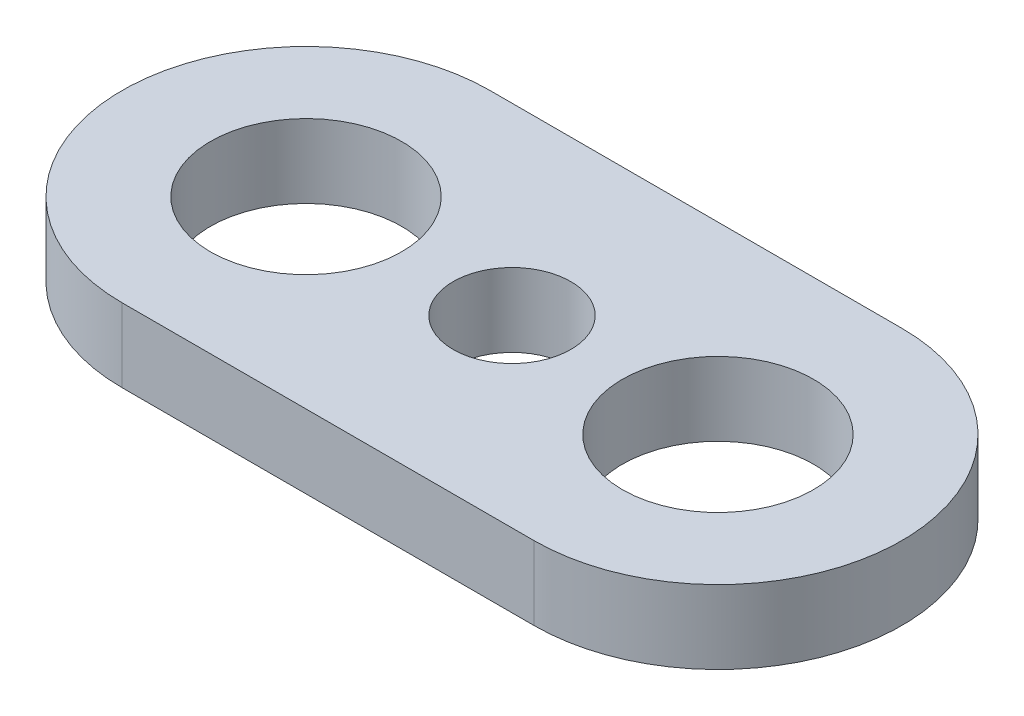
SolidWorks part; units mm, degrees
ref_plane "正面" through (0, 0, 0) normal (0, 0, 1) x (1, 0, 0)
ref_plane "平面" through (0, 0, 0) normal (0, 1, 0) x (1, 0, 0)
ref_plane "右側面" through (0, 0, 0) normal (1, 0, 0) x (0, 0, -1)
sketch "ｽｹｯﾁ1" plane through (0, 0, 0) normal (0, 1, 0) x (1, 0, 0)
  line L0 (-5.6, 0) -> (5.6, 0) construction
  line L1 (-5.6, 5) -> (5.6, 5)
  line L2 (-5.6, -5) -> (5.6, -5)
  arc A0 (-5.6, 5) -> (-5.6, -5) centre (-5.6, 0) ccw
  arc A1 (5.6, -5) -> (5.6, 5) centre (5.6, 0) ccw
  circle A2 centre (-5.6, 0) radius 2.6
  circle A3 centre (5.6, 0) radius 2.6
  circle A4 centre (0, 0) radius 1.6
  point P2 (0, 0)
  dimension "D2" = 5.2
  dimension "D3" = 5
  dimension "D4" = 3.2
  dimension "D1" = 11.2
extrude "ﾎﾞｽ - 押し出し1" add sketch "ｽｹｯﾁ1" along normal blind 2
